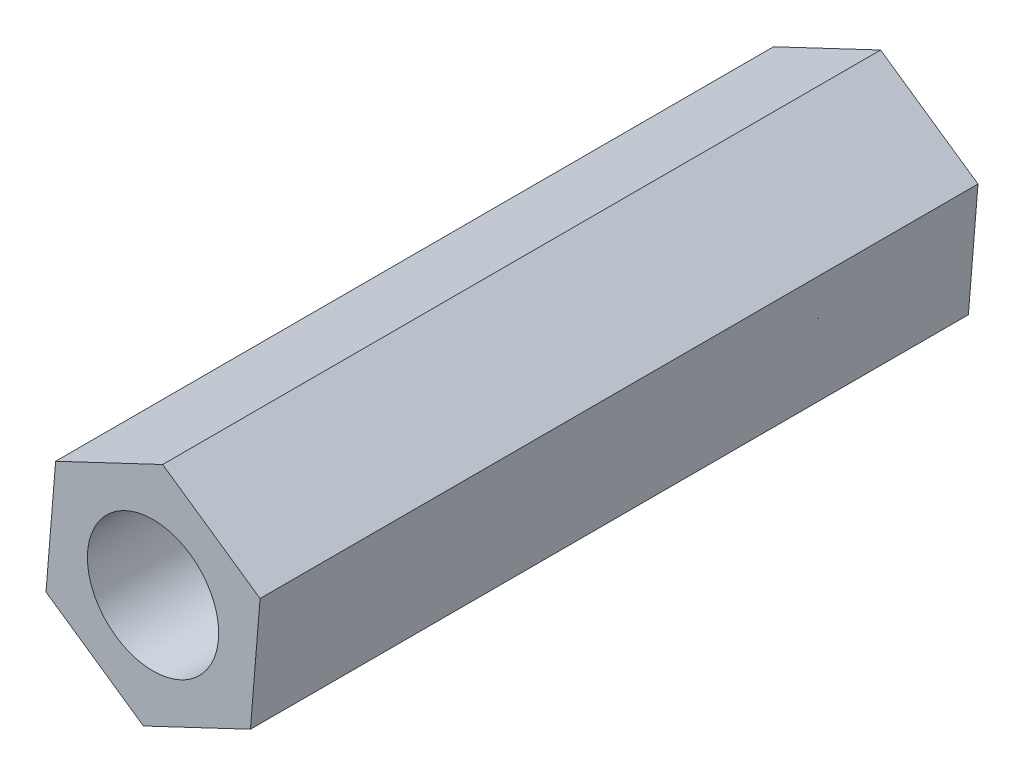
SolidWorks part; units mm, degrees
ref_plane "Front Plane" through (0, 0, 0) normal (0, 0, 1) x (1, 0, 0)
ref_plane "Top Plane" through (0, 0, 0) normal (0, 1, 0) x (1, 0, 0)
ref_plane "Right Plane" through (0, 0, 0) normal (1, 0, 0) x (0, 0, -1)
sketch "Sketch1" plane through (0, 0, 0) normal (0, 0, 1) x (1, 0, 0)
  line L1 (-2.3745, 1.6416) -> (-2.609, -1.2356)
  line L2 (-2.609, -1.2356) -> (-0.2344, -2.8772)
  line L3 (-0.2344, -2.8772) -> (2.3745, -1.6416)
  line L4 (2.3745, -1.6416) -> (2.609, 1.2356)
  line L5 (2.609, 1.2356) -> (0.2344, 2.8772)
  line L6 (0.2344, 2.8772) -> (-2.3745, 1.6416)
  circle A0 centre (0, 0) radius 2.5 construction
  dimension "D1" = 5
extrude "Boss-Extrude1" add sketch "Sketch1" along normal blind 5
sketch "Sketch2" plane through (0, 0, 5) normal (0, 0, 1) x (1, 0, 0)
  circle A0 centre (0, 0) radius 1.6
extrude "Cut-Extrude1" cut sketch "Sketch2" against normal blind 5
sketch "Sketch3" plane through (0, 0, 5) normal (0, 0, 1) x (1, 0, 0)
  line L1 (-0.2344, -2.8772) -> (2.3745, -1.6416)
  line L2 (2.3745, -1.6416) -> (2.609, 1.2356)
  line L3 (2.609, 1.2356) -> (0.2344, 2.8772)
  line L4 (0.2344, 2.8772) -> (-2.3745, 1.6416)
  line L5 (-2.3745, 1.6416) -> (-2.609, -1.2356)
  line L6 (-2.609, -1.2356) -> (-0.2344, -2.8772)
  circle A0 centre (0, 0) radius 2.5 construction
extrude "Boss-Extrude2" add sketch "Sketch3" along normal blind 12.5
sketch "Sketch4" plane through (0, 0, 5) normal (0, 0, -1) x (-1, 0, 0)
  circle A0 centre (0, 0) radius 1.6
extrude "Cut-Extrude2" cut sketch "Sketch4" against normal blind 12.5
